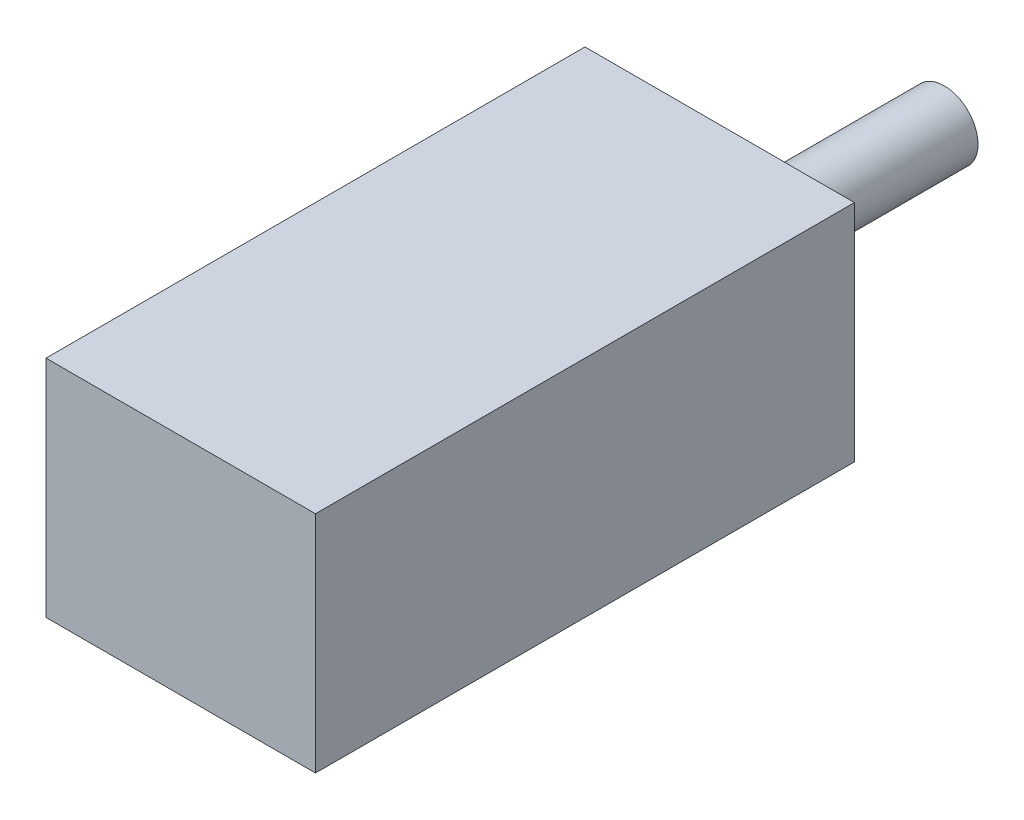
SolidWorks part; units mm, degrees
ref_plane "Front Plane" through (0, 0, 0) normal (0, 0, 1) x (1, 0, 0)
ref_plane "Top Plane" through (0, 0, 0) normal (0, 1, 0) x (1, 0, 0)
ref_plane "Right Plane" through (0, 0, 0) normal (1, 0, 0) x (0, 0, -1)
sketch "Sketch1" plane through (0, 0, 0) normal (0, 0, 1) x (1, 0, 0)
  line L1 (-6, 5) -> (6, 5)
  line L2 (-6, 5) -> (-6, -5)
  line L3 (-6, -5) -> (6, -5)
  line L4 (6, 5) -> (6, -5)
  line L5 (-6, 5) -> (6, -5) construction
  line L6 (-6, -5) -> (6, 5) construction
  point P0 (0, 0)
  dimension "D1" = 12
  dimension "D2" = 10
extrude "Boss-Extrude1" add sketch "Sketch1" along normal blind 24
sketch "Sketch2" plane through (0, 0, 0) normal (0, 0, -1) x (-1, 0, 0)
  circle A0 centre (0, 0) radius 1.5
  dimension "D1" = 3
extrude "Boss-Extrude2" add sketch "Sketch2" along normal blind 10
